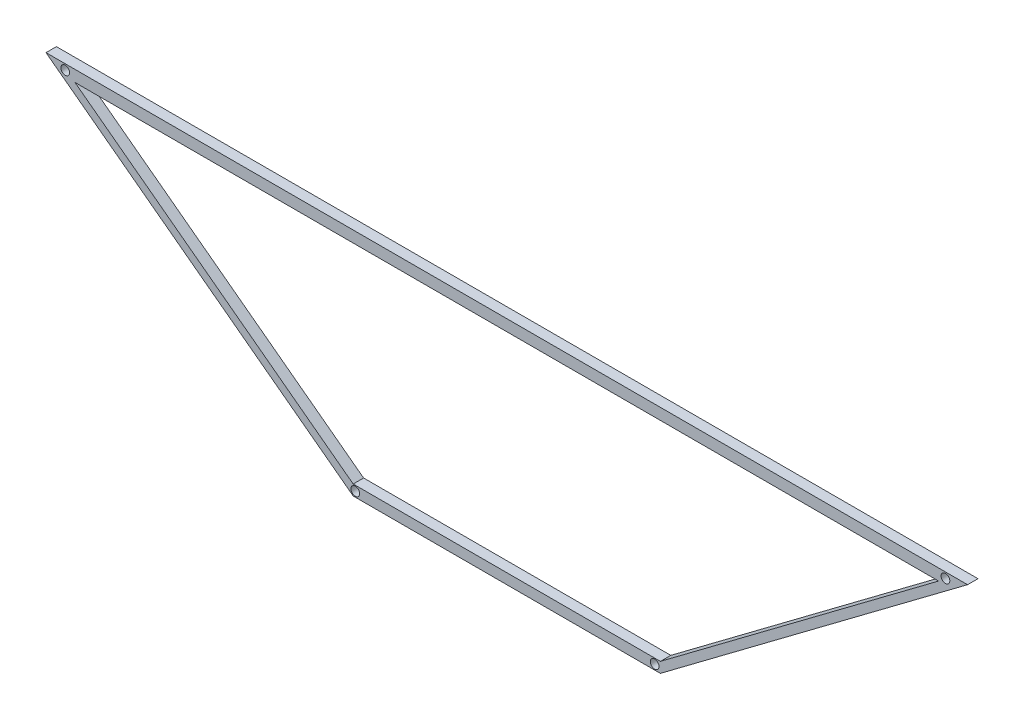
SolidWorks part; units mm, degrees
material "A500 Steel"
ref_plane "Front Plane" through (0, 0, 0) normal (0, 0, 1) x (1, 0, 0)
ref_plane "Top Plane" through (0, 0, 0) normal (0, 1, 0) x (1, 0, 0)
ref_plane "Right Plane" through (0, 0, 0) normal (1, 0, 0) x (0, 0, -1)
sketch "Sketch4" plane through (0, 0, 0) normal (0, 0, 1) x (1, 0, 0)
  line L0 (-225.8161, 70.0951) -> (974.1839, 70.0951)
  line L1 (174.1839, -229.9049) -> (574.1839, -229.9049)
  line L2 (-225.8161, 70.0951) -> (174.1839, -229.9049)
  line L3 (974.1839, 70.0951) -> (574.1839, -229.9049)
  line L4 (574.1839, -216.3449) -> (936.4474, 55.3527)
  line L5 (174.1839, -216.3449) -> (574.1839, -216.3449)
  line L6 (174.1839, -216.3449) -> (-188.0795, 55.3527)
  line L7 (936.4474, 55.3527) -> (-188.0795, 55.3527)
  dimension "D1" = 400
  dimension "D2" = 400
  dimension "D3" = 1200
  dimension "D4" = 300
  dimension "D5" = 13.56
  dimension "D6" = 14.7424
extrude "Boss-Extrude2" add sketch "Sketch4" along normal blind 13.56
sketch "Sketch5" plane through (0, 0, 13.56) normal (0, 0, 1) x (1, 0, 0)
  circle A0 centre (945.3399, 62.7778) radius 5.7
  circle A1 centre (-200.7894, 62.7778) radius 5.7
  circle A2 centre (176.9192, -223.073) radius 5.7
  circle A3 centre (566.6749, -223.073) radius 5.7
extrude "Cut-Extrude1" cut sketch "Sketch5" against normal through all
